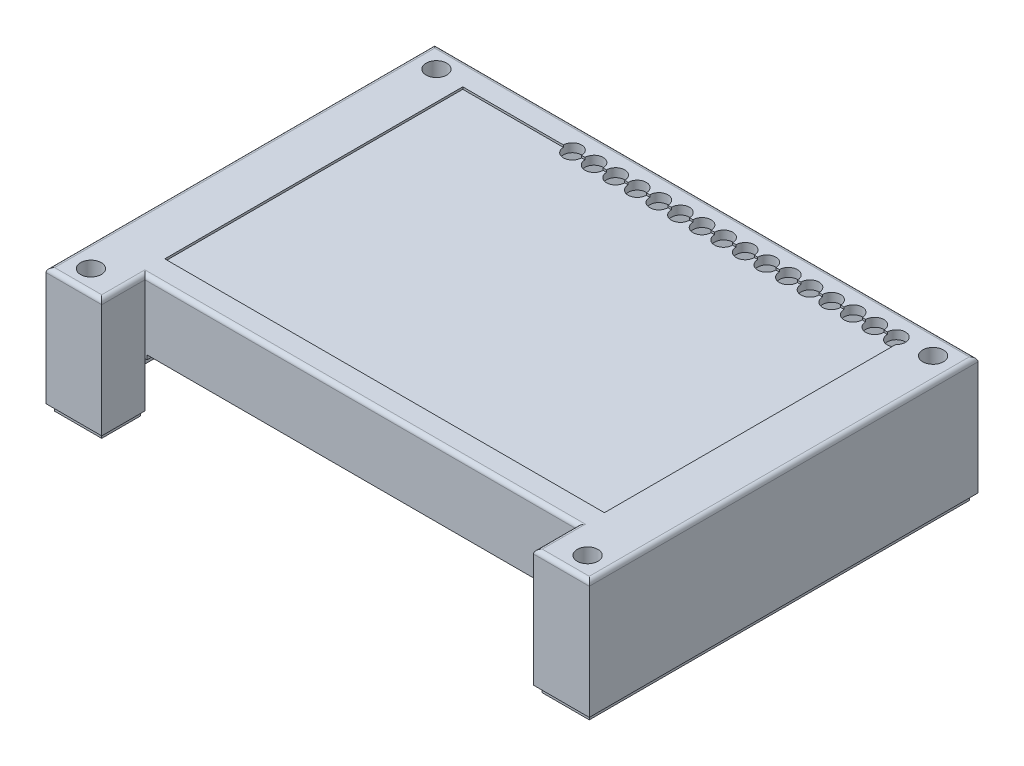
SolidWorks part; units mm, degrees
ref_plane "Спереди" through (0, 0, 0) normal (0, 0, 1) x (1, 0, 0)
ref_plane "Сверху" through (0, 0, 0) normal (0, 1, 0) x (1, 0, 0)
ref_plane "Справа" through (0, 0, 0) normal (1, 0, 0) x (0, 0, -1)
sketch "Эскиз1" plane through (0, 0, 0) normal (0, 1, 0) x (1, 0, 0)
  line L1 (62.9, -45) -> (-62.9, -45)
  line L2 (62.9, -45) -> (62.9, 45)
  line L3 (62.9, 45) -> (-62.9, 45)
  line L4 (-62.9, -45) -> (-62.9, 45)
  line L5 (62.9, -45) -> (-62.9, 45) construction
  line L6 (62.9, 45) -> (-62.9, -45) construction
  point P0 (0, 0)
  dimension "D1" = 125.8
  dimension "D2" = 90
extrude "Бобышка-Вытянуть1" add sketch "Эскиз1" along normal blind 28.8
sketch "Эскиз2" plane through (0, 28.8, 0) normal (0, 1, 0) x (1, 0, 0)
  line L0 (-62.9, -45) -> (62.9, -45) construction
  line L1 (-50, -50) -> (50, -50)
  line L2 (-50, -50) -> (-50, -35)
  line L3 (-50, -35) -> (50, -35)
  line L4 (50, -50) -> (50, -35)
  dimension "D1" = 100
  dimension "D2" = 50
  dimension "D3" = 5
  dimension "D4" = 10
extrude "Вырез-Вытянуть1" cut sketch "Эскиз2" against normal through all
shell "Оболочка1" thickness 2
sketch "Эскиз3" plane through (0, 0, 0) normal (0, -1, 0) x (1, 0, 0)
  line L0 (50, 35) -> (-50, 35) construction
  line L1 (-53, 35) -> (53, 35)
  line L2 (-53, 35) -> (-53, 32)
  line L3 (-53, 32) -> (53, 32)
  line L4 (53, 35) -> (53, 32)
  line L5 (52, 33) -> (-52, 33) construction
  line L6 (52, 43) -> (52, 33) construction
  line L7 (-52, 33) -> (-52, 43) construction
  dimension "D1" = 0
  dimension "D2" = 1
  dimension "D3" = 1
  dimension "D4" = 1
extrude "Вырез-Вытянуть2" cut sketch "Эскиз3" against normal blind 12
sketch "Эскиз4" plane through (0, 26.8, 0) normal (0, -1, 0) x (1, 0, 0)
  line L0 (-62.9, -45) -> (-62.9, 45) construction
  line L1 (-60.9, 43) -> (-53.9, 43)
  line L2 (-60.9, 43) -> (-60.9, 36)
  line L3 (-60.9, 36) -> (-58.9, 36)
  line L4 (-53.9, 43) -> (-53.9, 41)
  line L5 (60.9, 43) -> (53.9, 43)
  line L6 (60.9, 43) -> (60.9, 36)
  line L7 (60.9, 36) -> (58.9, 36)
  line L8 (53.9, 43) -> (53.9, 41)
  line L9 (-60.9, -43) -> (-53.9, -43)
  line L10 (-60.9, -43) -> (-60.9, -36)
  line L11 (-60.9, -36) -> (-58.9, -36)
  line L12 (-53.9, -43) -> (-53.9, -41)
  line L13 (60.9, -43) -> (53.9, -43)
  line L14 (60.9, -43) -> (60.9, -36)
  line L15 (60.9, -36) -> (58.9, -36)
  line L16 (53.9, -43) -> (53.9, -41)
  line L17 (62.9, -45) -> (-62.9, -45) construction
  line L18 (62.9, 45) -> (62.9, -45) construction
  line L19 (-62.9, 45) -> (-50, 45) construction
  line L20 (50, 45) -> (62.9, 45) construction
  arc A0 (58.9, 36) -> (53.9, 41) centre (58.9, 41) cw
  arc A1 (58.9, -36) -> (53.9, -41) centre (58.9, -41) ccw
  arc A2 (-58.9, -36) -> (-53.9, -41) centre (-58.9, -41) cw
  arc A3 (-58.9, 36) -> (-53.9, 41) centre (-58.9, 41) ccw
  point P26 (59.9, -36)
  dimension "D9" = 5
  dimension "D1" = 9
  dimension "D2" = 9
  dimension "D3" = 9
  dimension "D4" = 9
  dimension "D5" = 9
  dimension "D6" = 9
  dimension "D7" = 9
  dimension "D8" = 9
extrude "Бобышка-Вытянуть2" add sketch "Эскиз4" along normal up to surface (26.8 mm away) up to face at (0, 0, 19.75)
sketch "Эскиз5" plane through (0, 0, 0) normal (0, -1, 0) x (1, 0, 0)
  line L0 (-62.9, -45) -> (-62.9, 45) construction
  line L1 (-62.9, 45) -> (-50, 45) construction
  line L2 (62.9, 45) -> (62.9, -45) construction
  line L3 (50, 45) -> (62.9, 45) construction
  line L4 (62.9, -45) -> (-62.9, -45) construction
  circle A0 centre (-57.5, 40) radius 1.75
  circle A1 centre (57.5, 40) radius 1.75
  circle A2 centre (57.5, -40) radius 1.75
  circle A3 centre (-57.5, -40) radius 1.75
  dimension "D3" = 3.5
  dimension "D6" = 3.5
  dimension "D9" = 3.5
  dimension "D12" = 3.5
  dimension "D1" = 5.4
  dimension "D2" = 5
  dimension "D4" = 5.4
  dimension "D5" = 5
  dimension "D7" = 5.4
  dimension "D8" = 5
  dimension "D10" = 5.4
  dimension "D11" = 5
extrude "Вырез-Вытянуть3" cut sketch "Эскиз5" against normal through all
sketch "Эскиз6" plane through (0, 28.8, 0) normal (0, 1, 0) x (1, 0, 0)
  circle A0 centre (-57.5, 40) radius 2.4
  circle A1 centre (57.5, 40) radius 2.4
  circle A2 centre (-57.5, -40) radius 2.4
  circle A3 centre (57.5, -40) radius 2.4
  dimension "D1" = 4.8
  dimension "D2" = 4.8
  dimension "D3" = 4.8
  dimension "D4" = 4.8
  dimension "D5" = 115
extrude "Вырез-Вытянуть4" cut sketch "Эскиз6" against normal blind 27
sketch "Эскиз7" plane through (0, 28.8, 0) normal (0, 1, 0) x (1, 0, 0)
  line L0 (62.9, 45) -> (-62.9, 45) construction
  line L1 (-50.9, 39.5) -> (50.9, 39.5)
  line L2 (-50.9, 39.5) -> (-50.9, -29.5)
  line L3 (-50.9, -29.5) -> (50.9, -29.5)
  line L4 (50.9, 39.5) -> (50.9, -29.5)
  line L5 (50, -35) -> (-50, -35) construction
  line L6 (62.9, -45) -> (62.9, 45) construction
  line L7 (-62.9, 45) -> (-62.9, -45) construction
  dimension "D1" = 5.5
  dimension "D2" = 5.5
  dimension "D3" = 12
  dimension "D4" = 12
extrude "Вырез-Вытянуть5" cut sketch "Эскиз7" against normal blind 0.5
fillet "Скругление1" radius 1 8 edges at (-56.45, 28.8, 45) (-50, 28.8, 40) (0, 28.8, 35) (50, 28.8, 40) (56.45, 28.8, 45) (62.9, 28.8, 0) (0, 28.8, -45) (-62.9, 28.8, 0)
sketch "Эскиз8" plane through (0, 0, 0) normal (0, -1, 0) x (1, 0, 0)
  line L0 (-51, 32) -> (-51, 44)
  line L1 (-51, 44) -> (-61.9, 44)
  line L2 (-61.9, 44) -> (-61.9, -44)
  line L3 (-61.9, -44) -> (61.9, -44)
  line L4 (61.9, -44) -> (61.9, 44)
  line L5 (61.9, 44) -> (51, 44)
  line L6 (51, 44) -> (51, 32)
  line L7 (51, 32) -> (49, 32)
  line L8 (49, 32) -> (49, 46)
  line L9 (49, 46) -> (63.9, 46)
  line L10 (63.9, 46) -> (63.9, -46)
  line L11 (63.9, -46) -> (-63.9, -46)
  line L12 (-63.9, -46) -> (-63.9, 46)
  line L13 (-63.9, 46) -> (-49, 46)
  line L14 (-49, 46) -> (-49, 32)
  line L15 (-49, 32) -> (-51, 32)
  line L16 (-62.9, -45) -> (-62.9, 45) construction
  line L17 (-62.9, 45) -> (-50, 45) construction
  line L18 (-50, 35) -> (-50, 45) construction
  line L19 (52, 33) -> (-52, 33) construction
  line L20 (62.9, -45) -> (-62.9, -45) construction
  line L21 (60.9, 36) -> (60.9, -36) construction
  line L22 (62.9, 45) -> (62.9, -45) construction
  line L23 (50, 45) -> (62.9, 45) construction
  line L24 (52, 43) -> (52, 35) construction
  line L25 (50, 45) -> (50, 35) construction
  dimension "D1" = 1
  dimension "D2" = 1
  dimension "D3" = 1
  dimension "D4" = 1
  dimension "D5" = 1
  dimension "D6" = 1
  dimension "D7" = 1
  dimension "D8" = 1
  dimension "D9" = 1
  dimension "D10" = 1
  dimension "D11" = 1
  dimension "D12" = 1
  dimension "D13" = 1
  dimension "D14" = 1
  dimension "D15" = 1
  dimension "D16" = 1
extrude "Вырез-Вытянуть6" cut sketch "Эскиз8" against normal blind 1.5
sketch "Эскиз9" plane through (0, 0, 35) normal (0, 0, 1) x (1, 0, 0)
  line L0 (50, 12) -> (-50, 12) construction
  line L1 (-49.5, 13) -> (49.5, 13)
  line L2 (-49.5, 13) -> (-49.5, 11)
  line L3 (-49.5, 11) -> (49.5, 11)
  line L4 (49.5, 13) -> (49.5, 11)
  line L5 (-50, 1.5) -> (-50, 27.8) construction
  line L6 (50, 27.8) -> (50, 1.5) construction
  dimension "D1" = 1
  dimension "D2" = 0.5
  dimension "D3" = 0.5
  dimension "D4" = 1
extrude "Вырез-Вытянуть7" cut sketch "Эскиз9" against normal blind 3
sketch "Эскиз10" plane through (0, 0, -45) normal (0, 0, -1) x (-1, 0, 0)
  line L0 (62.9, 27.8) -> (62.9, 1.5) construction
  line L1 (34.9, 14) -> (51.9, 14)
  line L2 (34.9, 14) -> (34.9, -1)
  line L3 (34.9, -1) -> (51.9, -1)
  line L4 (51.9, 14) -> (51.9, -1)
  line L5 (-61.9, 1.5) -> (61.9, 1.5) construction
  line L6 (-61.9, 0) -> (61.9, 0) construction
  dimension "D1" = 11
  dimension "D2" = 12.5
  dimension "D3" = 1
  dimension "D4" = 28
extrude "Вырез-Вытянуть8" cut sketch "Эскиз10" against normal blind 3
sketch "Эскиз11" plane through (0, 0, -45) normal (0, 0, -1) x (-1, 0, 0)
  line L0 (-62.9, 27.8) -> (-62.9, 1.5) construction
  line L1 (-52.5, 13.5) -> (28.5, 13.5)
  line L2 (-52.5, 13.5) -> (-52.5, -1)
  line L3 (-52.5, -1) -> (28.5, -1)
  line L4 (28.5, 13.5) -> (28.5, -1)
  line L5 (-61.9, 0) -> (34.9, 0) construction
  line L6 (-61.9, 1.5) -> (34.9, 1.5) construction
  dimension "D1" = 10.4
  dimension "D2" = 1
  dimension "D3" = 12
  dimension "D4" = 91.4
extrude "Вырез-Вытянуть9" cut sketch "Эскиз11" against normal blind 3
sketch "Эскиз12" plane through (0, 28.8, 0) normal (0, 1, 0) x (1, 0, 0)
  line L0 (-62.9, 45) -> (62.9, 45) construction
  line L1 (62.9, 45) -> (62.9, -45) construction
  circle A0 centre (49.5, 39.5) radius 2.1
  dimension "D3" = 4.2
  dimension "D1" = 5.5
  dimension "D2" = 13.4
extrude "Вырез-Вытянуть10" cut sketch "Эскиз12" against normal blind 3
pattern_linear "Линейный массив1" count 16 spacing 5 along (-1, 0, 0) of "Вырез-Вытянуть10"
